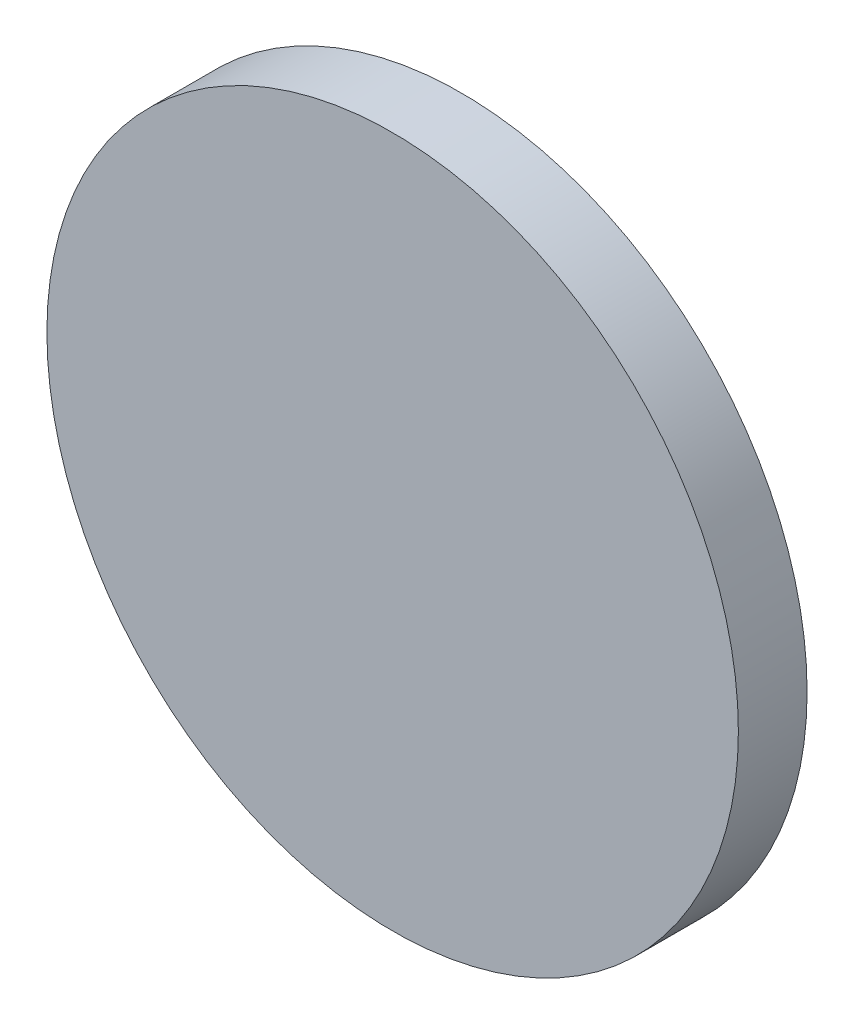
SolidWorks part; units mm, degrees
ref_plane "Спереди" through (0, 0, 0) normal (0, 0, 1) x (1, 0, 0)
ref_plane "Сверху" through (0, 0, 0) normal (0, 1, 0) x (1, 0, 0)
ref_plane "Справа" through (0, 0, 0) normal (1, 0, 0) x (0, 0, -1)
sketch "Эскиз1" plane through (0, 0, 0) normal (0, 0, 1) x (1, 0, 0)
  circle A0 centre (-55.6085, 37.6381) radius 100.6234
extrude "Бобышка-Вытянуть1" add sketch "Эскиз1" along normal blind 20
